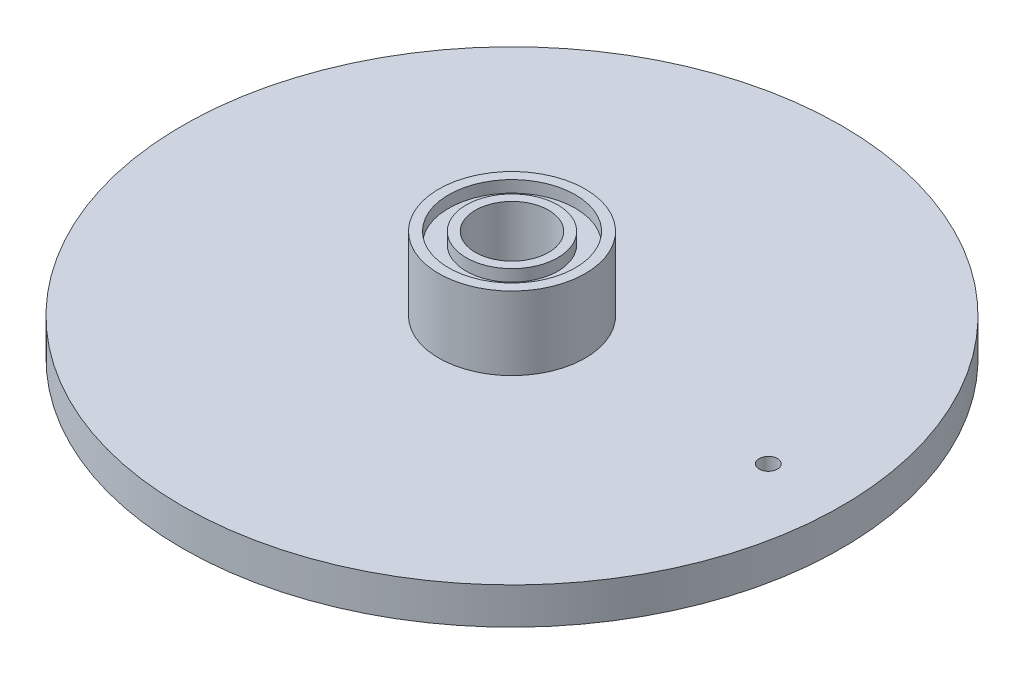
SolidWorks part; units mm, degrees
ref_plane "Front Plane" through (0, 0, 0) normal (0, 0, 1) x (1, 0, 0)
ref_plane "Top Plane" through (0, 0, 0) normal (0, 1, 0) x (1, 0, 0)
ref_plane "Right Plane" through (0, 0, 0) normal (1, 0, 0) x (0, 0, -1)
sketch "Sketch1" plane through (0, 0, 0) normal (0, 0, 1) x (1, 0, 0)
  line L0 (-6.35, 0) -> (-52.5145, 0)
  line L1 (-57.15, 0) -> (-57.15, 6.35)
  line L2 (-57.15, 6.35) -> (-12.7, 6.35)
  line L3 (-12.7, 6.35) -> (-12.7, 19.05)
  line L4 (-12.7, 19.05) -> (-10.9855, 19.05)
  line L5 (-6.35, 19.05) -> (-6.35, 9.398)
  line L6 (0, 0) -> (0, 29.7484) construction
  line L7 (-57.15, 0) -> (-55.5625, 0)
  line L8 (-55.5625, 0) -> (-55.5625, 2.032)
  line L9 (-55.5625, 2.032) -> (-52.5145, 2.032)
  line L10 (-52.5145, 2.032) -> (-52.5145, 0)
  line L11 (-10.9855, 19.05) -> (-10.9855, 17.018)
  line L12 (-10.9855, 17.018) -> (-7.9375, 17.018)
  line L13 (-7.9375, 17.018) -> (-7.9375, 19.05)
  line L14 (-7.9375, 19.05) -> (-6.35, 19.05)
  line L15 (-6.35, 0) -> (-6.35, 6.35)
  line L16 (-6.35, 6.35) -> (-8.382, 6.35)
  line L17 (-8.382, 6.35) -> (-8.382, 9.398)
  line L18 (-8.382, 9.398) -> (-6.35, 9.398)
  dimension "D1" = 6.35
  dimension "D2" = 57.15
  dimension "D3" = 6.35
  dimension "D4" = 6.35
  dimension "D5" = 12.7
  dimension "D6" = 2.032
  dimension "D7" = 3.048
  dimension "D8" = 1.5875
  dimension "D9" = 2.032
  dimension "D10" = 3.048
  dimension "D11" = 1.5875
  dimension "D12" = 2.032
  dimension "D13" = 3.048
  dimension "D14" = 6.35
revolve "Revolve1" add sketch "Sketch1" angle 360 about L6
hole_wizard "1/8 (0.125) Diameter Hole1" positions "Sketch2" profile "Sketch3" hole size "1/8" standard "ANSI Inch"
sketch "Sketch2" plane through (0, 6.35, 0) normal (0, 1, 0) x (1, 0, 0)
  line L0 (0, 0) -> (44.45, 0) construction
  point P0 (44.45, 0)
  point P6 (47.6402, 0)
  dimension "D1" = 44.45
sketch "Sketch3" plane through (44.45, 6.35, 0) normal (1, 0, 0) x (0, 0, 1)
  line L0 (0, 0) -> (0, 4.1289)
  line L1 (0, 4.1289) -> (1.5875, 3.175)
  line L2 (1.5875, 3.175) -> (1.5875, 0)
  line L5 (1.5875, 0) -> (0, 0)
  line L10 (0, 4.1289) -> (-1.5875, 3.175) construction
  line L11 (0, -6.35) -> (0, 107.95) construction
  dimension "Hole Dia." = 3.175
  dimension "Hole Depth" = 3.175
  dimension "Drill Angle" = 118
